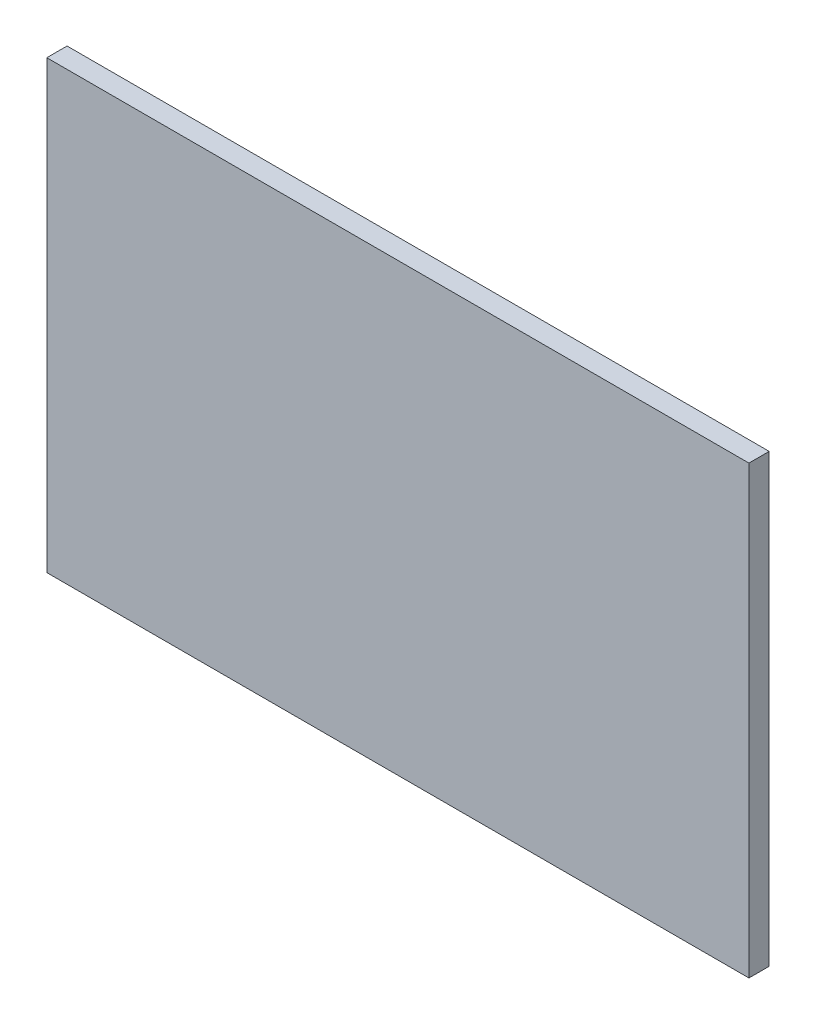
SolidWorks part; units mm, degrees
ref_plane "Front Plane" through (0, 0, 0) normal (0, 0, 1) x (1, 0, 0)
ref_plane "Top Plane" through (0, 0, 0) normal (0, 1, 0) x (1, 0, 0)
ref_plane "Right Plane" through (0, 0, 0) normal (1, 0, 0) x (0, 0, -1)
sketch "Sketch1" plane through (0, 0, 0) normal (0, 0, 1) x (1, 0, 0)
  line L1 (-109.982, -69.85) -> (109.982, -69.85)
  line L2 (-109.982, -69.85) -> (-109.982, 69.85)
  line L3 (-109.982, 69.85) -> (109.982, 69.85)
  line L4 (109.982, -69.85) -> (109.982, 69.85)
  line L5 (-109.982, -69.85) -> (109.982, 69.85) construction
  line L6 (-109.982, 69.85) -> (109.982, -69.85) construction
  point P0 (0, 0)
  dimension "D1" = 219.964
  dimension "D2" = 139.7
extrude "Boss-Extrude1" add sketch "Sketch1" along normal blind 6.35
